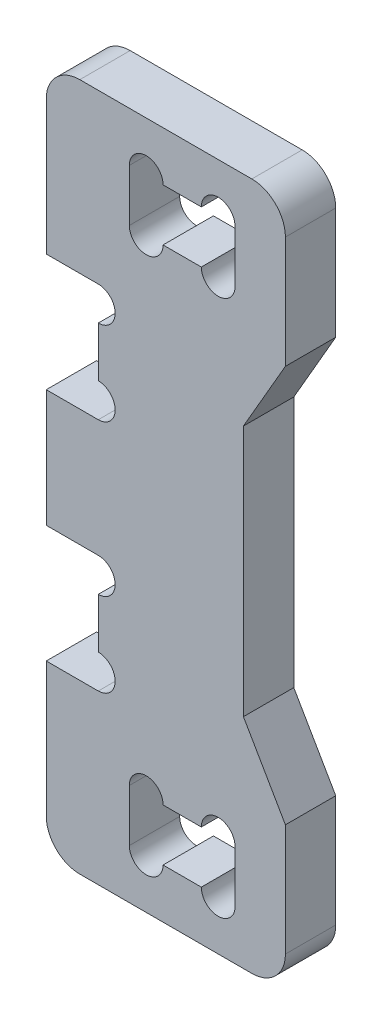
SolidWorks part; units mm, degrees
material "Thornel Mat VMA"
ref_plane "前视基准面" through (0, 0, 0) normal (0, 0, 1) x (1, 0, 0)
ref_plane "上视基准面" through (0, 0, 0) normal (0, 1, 0) x (1, 0, 0)
ref_plane "右视基准面" through (0, 0, 0) normal (1, 0, 0) x (0, 0, -1)
sketch "草图1" plane through (0, 0, 0) normal (0, 0, 1) x (1, 0, 0)
  line L0 (-7.125, 20.5) -> (-7.125, 10.5)
  line L1 (7.125, -20.5) -> (-7.125, -20.5)
  line L2 (7.125, -20.5) -> (7.125, -11.8301)
  line L3 (7.125, 20.5) -> (-7.125, 20.5)
  line L4 (-7.125, -20.5) -> (-7.125, 20.5) construction
  line L5 (7.125, -20.5) -> (-7.125, 20.5) construction
  line L6 (7.125, 20.5) -> (-7.125, -20.5) construction
  line L7 (4.125, 14.45) -> (-2.175, 14.45)
  line L8 (4.125, 14.45) -> (4.125, 17.55)
  line L9 (4.125, 17.55) -> (-2.175, 17.55)
  line L10 (-2.175, 14.45) -> (-2.175, 17.55)
  line L11 (4.125, 14.45) -> (-2.175, 17.55) construction
  line L12 (4.125, 17.55) -> (-2.175, 14.45) construction
  line L13 (-7.125, 10.5) -> (-4.025, 10.5)
  line L14 (-4.025, 10.5) -> (-4.025, 3.5)
  line L15 (-4.025, 3.5) -> (-7.125, 3.5)
  line L16 (-7.125, 3.5) -> (-7.125, -3.5)
  line L17 (-7.125, 0) -> (0, 0) construction
  line L18 (-4.025, 7) -> (-30.0758, 7) construction
  line L19 (-4.025, -3.5) -> (-7.125, -3.5)
  line L20 (-4.025, -10.5) -> (-4.025, -3.5)
  line L21 (-7.125, -10.5) -> (-4.025, -10.5)
  line L22 (-7.125, -20.5) -> (-7.125, -10.5)
  line L23 (-4.025, -7) -> (-30.0758, -7) construction
  line L24 (4.125, -17.55) -> (-2.175, -17.55)
  line L25 (-2.175, -14.45) -> (-2.175, -17.55)
  line L26 (4.125, -14.45) -> (-2.175, -14.45)
  line L27 (4.125, -14.45) -> (4.125, -17.55)
  line L28 (7.125, 11.8301) -> (4.625, 7.5)
  line L33 (4.625, 7.5) -> (4.625, -7.5)
  line L34 (7.125, -11.8301) -> (4.625, -7.5)
  line L35 (7.125, 11.8301) -> (7.125, 20.5)
  circle A0 centre (-1.17, 14.45) radius 1.005
  circle A1 centre (3.12, 14.45) radius 1.005
  circle A2 centre (-1.17, 17.55) radius 1.005
  circle A3 centre (3.12, 17.55) radius 1.005
  circle A4 centre (-4.025, 9.495) radius 1.005
  circle A5 centre (-4.025, 4.505) radius 1.005
  circle A6 centre (-4.025, -4.505) radius 1.005
  circle A7 centre (-4.025, -9.495) radius 1.005
  circle A8 centre (3.12, -17.55) radius 1.005
  circle A9 centre (3.12, -14.45) radius 1.005
  circle A10 centre (-1.17, -14.45) radius 1.005
  circle A11 centre (-1.17, -17.55) radius 1.005
  point P0 (0, 0)
  point P6 (0.975, 16)
  dimension "D10" = 2.01
  dimension "D1" = 3.1
  dimension "D2" = 6.3
  dimension "D3" = 3.1
  dimension "D4" = 14
  dimension "D5" = 7
  dimension "D6" = 9
  dimension "D7" = 41
  dimension "D8" = 5
  dimension "D9" = 3
  dimension "D11" = 2.5
  dimension "D12" = 15
  dimension "D13" = 30
extrude "凸台-拉伸1" add sketch "草图1" along normal blind 3 contours A7 L21 L22 L1 L2 L3 L0 L13 A4 L14 A5 L15 L16 L19 A6 L20 A3 L8 A1 L7 A0 L10 A2 L9 L24 A11 L25 A10 L26 A9 L27 A8
fillet "圆角1" radius 2 4 edges at (-7.125, -20.5, 1.5) (7.125, -20.5, 1.5) (-7.125, 20.5, 1.5) (7.125, 20.5, 1.5)
